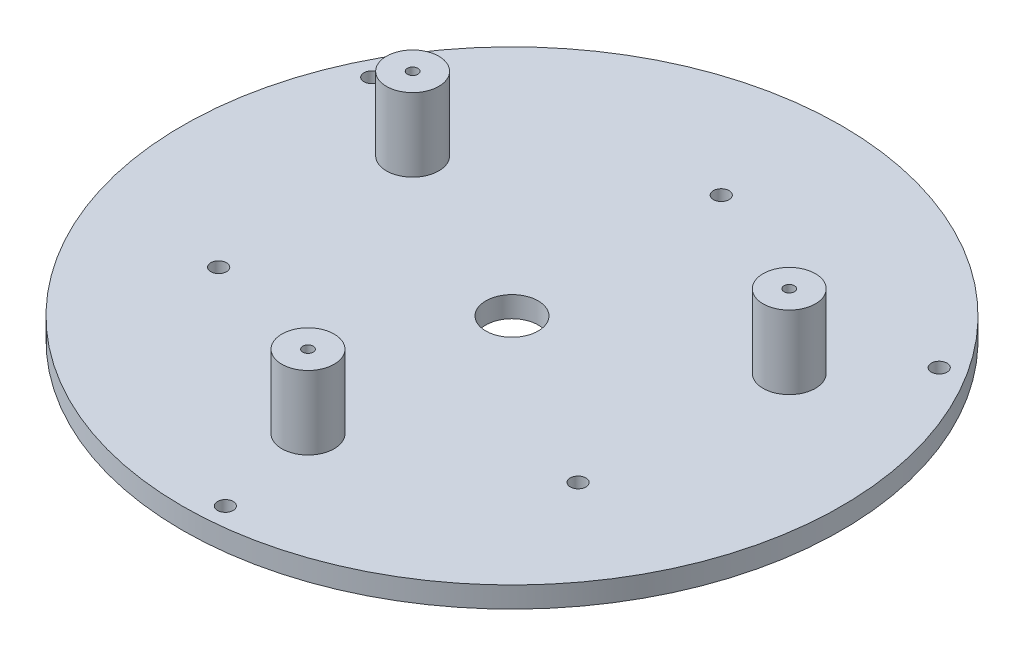
SolidWorks part; units mm, degrees
ref_plane "Front Plane" through (0, 0, 0) normal (0, 0, 1) x (1, 0, 0)
ref_plane "Top Plane" through (0, 0, 0) normal (0, 1, 0) x (1, 0, 0)
ref_plane "Right Plane" through (0, 0, 0) normal (1, 0, 0) x (0, 0, -1)
sketch "Sketch2" plane through (0, 0, 0) normal (0, 1, 0) x (1, 0, 0)
  circle A0 centre (0, 0) radius 63
  dimension "D1" = 126
extrude "Boss-Extrude2" add sketch "Sketch2" along normal blind 4
sketch "Sketch3" plane through (0, 4, 0) normal (0, 1, 0) x (1, 0, 0)
  circle A0 centre (0, 0) radius 5
  dimension "D1" = 10
extrude "Cut-Extrude1" cut sketch "Sketch3" against normal up to surface (4 mm away) up to face at (0, 0, 63)
sketch "Sketch4" plane through (0, 4, 0) normal (0, 1, 0) x (1, 0, 0)
  circle A0 centre (-36, 17) radius 5
  circle A1 centre (36, 17) radius 5
  circle A2 centre (0, -39) radius 5
  circle A4 centre (-36, 17) radius 1
  circle A5 centre (36, 17) radius 1
  circle A6 centre (0, -39) radius 1
  dimension "D2" = 2
  dimension "D1" = 10
extrude "Boss-Extrude3" add sketch "Sketch4" along normal blind 14
sketch "Sketch5" plane through (0, 4, 0) normal (0, 1, 0) x (1, 0, 0)
  circle A0 centre (33.8886, -21.25) radius 1.5
  circle A1 centre (-36.0998, -19.9734) radius 1.5
  circle A2 centre (0, 40) radius 1.5
  dimension "D6" = 3
  dimension "D1" = 70
  dimension "D2" = 70
  dimension "D3" = 70
  dimension "D4" = 40
  dimension "D5" = 40
extrude "Cut-Extrude3" cut sketch "Sketch5" against normal up to surface (4 mm away) up to face at (0, 0, 5)
sketch "Sketch7" plane through (0, 0, 0) normal (0, -1, 0) x (1, 0, 0)
  circle A0 centre (4.0632, 58.8599) radius 1.5
  circle A1 centre (-52.9095, -26.1071) radius 1.5
  circle A2 centre (49.3905, -32.2735) radius 1.5
  dimension "D6" = 3
  dimension "D1" = 59
  dimension "D2" = 59
  dimension "D3" = 59
  dimension "D4" = 102.3
  dimension "D5" = 102.3
extrude "Cut-Extrude6" cut sketch "Sketch7" against normal up to surface (4 mm away) up to face at (33.8886, 4, 22.75)
